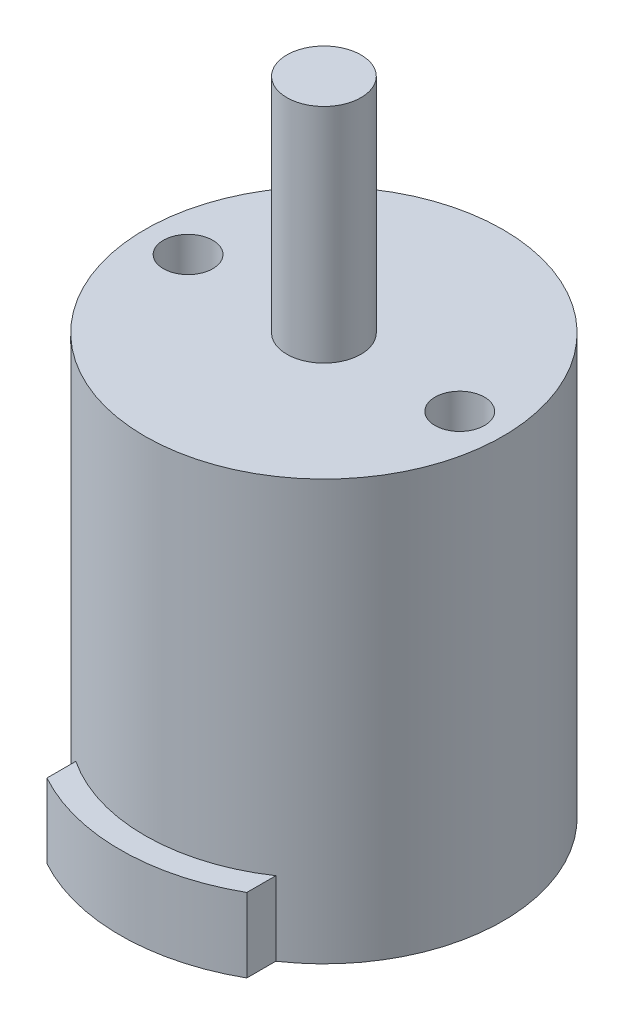
SolidWorks part; units mm, degrees
ref_plane "前视基准面" through (0, 0, 0) normal (0, 0, 1) x (1, 0, 0)
ref_plane "上视基准面" through (0, 0, 0) normal (0, 1, 0) x (1, 0, 0)
ref_plane "右视基准面" through (0, 0, 0) normal (1, 0, 0) x (0, 0, -1)
sketch "草图1" plane through (0, 0, 0) normal (0, 1, 0) x (1, 0, 0)
  circle A0 centre (0, 0) radius 7.25
  dimension "D1" = 14.5
extrude "凸台-拉伸1" add sketch "草图1" along normal blind 17
sketch "草图2" plane through (0, 17, 0) normal (0, 1, 0) x (1, 0, 0)
  circle A0 centre (0, 0) radius 1.5
  dimension "D1" = 3
extrude "凸台-拉伸2" add sketch "草图2" along normal blind 9
sketch "草图3" plane through (0, 0, 0) normal (0, -1, 0) x (1, 0, 0)
  line L0 (-4, 7.2154) -> (-4, 6.0068)
  line L1 (-4, 6.0068) -> (4.0597, 6.0068)
  line L2 (4.0597, 6.0068) -> (4.0597, 7.182)
  arc A0 (4.0597, 7.182) -> (-4, 7.2154) centre (0, 0) ccw
  circle A1 centre (0, 0) radius 7.25 construction
  dimension "D1" = 1
  dimension "D2" = 4
extrude "凸台-拉伸3" add sketch "草图3" against normal blind 3
sketch "草图4" plane through (0, 17, 0) normal (0, 1, 0) x (1, 0, 0)
  circle A0 centre (5.5, 0) radius 1
  circle A1 centre (-5.5, 0) radius 1
  dimension "D1" = 2
  dimension "D3" = 2
  dimension "D4" = 5.5
  dimension "D2" = 5.5
extrude "切除-拉伸1" cut sketch "草图4" against normal blind 3
